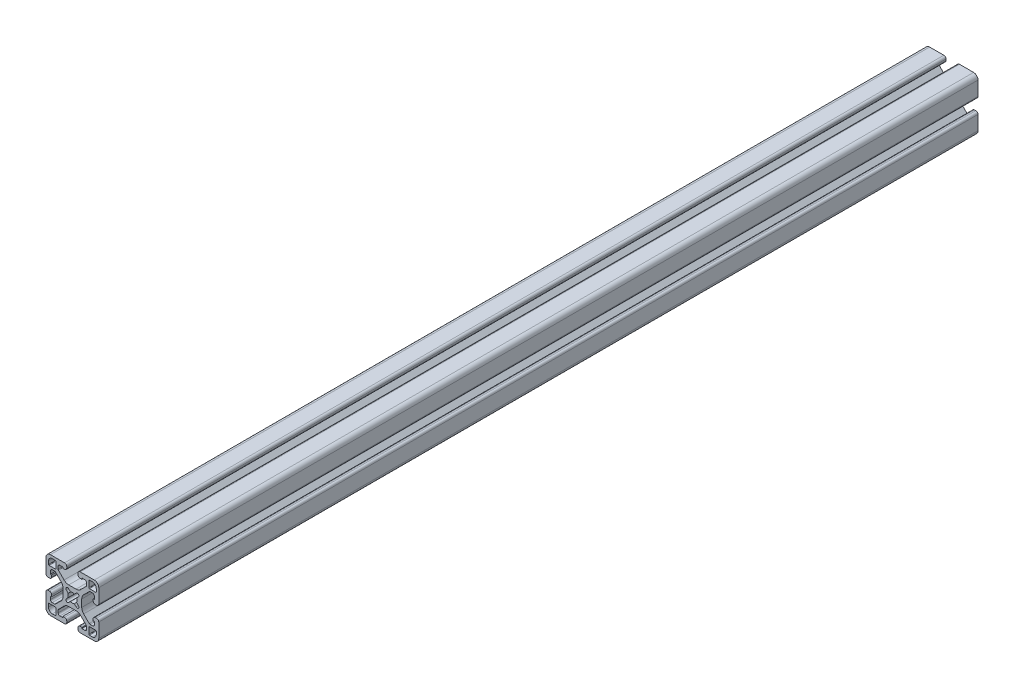
SolidWorks part; units mm, degrees
ref_plane "Front Plane" through (0, 0, 0) normal (0, 0, 1) x (1, 0, 0)
ref_plane "Top Plane" through (0, 0, 0) normal (0, 1, 0) x (1, 0, 0)
ref_plane "Right Plane" through (0, 0, 0) normal (1, 0, 0) x (0, 0, -1)
sketch "Sketch2" plane through (0, 0, 0) normal (0, 0, 1) x (1, 0, 0)
  line L0 (0, 19.05) -> (0, -19.05) construction
  line L1 (-19.05, 0) -> (19.05, 0) construction
  line L2 (4.064, -19.05) -> (19.05, -19.05)
  line L3 (19.05, -19.05) -> (19.05, -4.064)
  line L4 (4.064, -19.05) -> (4.064, -14.986)
  line L5 (4.064, -14.986) -> (12.8307, -14.986)
  line L6 (12.8307, -14.986) -> (4.6011, -6.7564)
  line L7 (0, 0) -> (19.05, -19.05) construction
  line L8 (19.05, -4.064) -> (14.986, -4.064)
  line L9 (14.986, -4.064) -> (14.986, -12.8307)
  line L10 (14.986, -12.8307) -> (6.7564, -4.6011)
  circle A0 centre (0, 0) radius 3.3274
  arc A1 (8.4883, -14.986) -> (9.7602, -11.9154) centre (8.4883, -13.1873) ccw construction
  point P8 (0, -6.7564)
  point P20 (0, 19.05)
  point P28 (19.05, 0)
  dimension "D1" = 3.048
  dimension "Center Hole Diameter" = 6.6548
  dimension "Rail Height" = 38.1
  dimension "Rail Width" = 38.1
  dimension "T Slot Width" = 8.128
  dimension "Slot Inner Width" = 20.574
  dimension "Thickness" = 4.064
  dimension "T Slot Depth" = 12.2936
sketch "Sketch3" plane through (0, 0, 0) normal (1, 0, 0) x (0, 0, -1)
  line L0 (-317.5, -19.05) -> (317.5, -19.05) construction
  line L1 (-274.066, 0) -> (274.066, 0) construction
  point P6 (-295.783, -19.05)
  dimension "Length" = 635
  dimension "D1" = 548.132
  dimension "Bore Hole Center to End of Rail" = 21.717
sketch "Sketch4" plane through (0, 0, 0) normal (0, 0, 1) x (1, 0, 0)
  line L1 (2.73, -4.3464) -> (1.4014, -3.0179)
  line L2 (15.8242, -6.858) -> (15.8242, -9.017)
  line L3 (14.5542, -10.287) -> (12.8105, -10.287)
  line L7 (4.3464, -2.73) -> (3.0179, -1.4014)
  line L9 (0, 0) -> (4.3464, -4.3464) construction
  line L23 (17.4752, -4.064) -> (16.5608, -4.064)
  line L24 (14.986, -5.6388) -> (14.986, -6.858)
  line L25 (12.1819, -10.0266) -> (8.1476, -5.9923)
  line L26 (6.7564, -2.6337) -> (6.7564, 0)
  line L27 (6.7564, 0) -> (3.3274, 0)
  line L28 (-19.05, 0) -> (19.05, 0) construction
  line L29 (0, -3.3274) -> (0, -6.7564)
  line L30 (0, 19.05) -> (0, -19.05) construction
  line L31 (0, -6.7564) -> (2.6337, -6.7564)
  line L32 (5.9923, -8.1476) -> (10.0266, -12.1819)
  line L33 (10.287, -12.8105) -> (10.287, -14.5542)
  line L34 (9.017, -15.8242) -> (6.858, -15.8242)
  line L35 (6.858, -15.8242) -> (6.858, -14.986)
  line L36 (6.858, -14.986) -> (5.6388, -14.986)
  line L37 (4.064, -16.5608) -> (4.064, -17.4752)
  line L39 (14.986, -6.858) -> (15.8242, -6.858)
  line L43 (14.986, -12.8307) -> (6.7564, -4.6011) construction
  line L44 (12.8307, -14.986) -> (4.6011, -6.7564) construction
  line L45 (15.875, -19.05) -> (5.6388, -19.05)
  line L46 (4.064, -19.05) -> (19.05, -19.05) construction
  line L48 (19.05, -15.875) -> (19.05, -5.6388)
  line L49 (19.05, -19.05) -> (19.05, -4.064) construction
  line L51 (4.064, -19.05) -> (4.064, -14.986) construction
  line L52 (19.05, -4.064) -> (14.986, -4.064) construction
  line L53 (4.064, -14.986) -> (12.8307, -14.986) construction
  arc A1 (15.875, -19.05) -> (19.05, -15.875) centre (15.875, -15.875) ccw
  arc A10 (9.017, -15.8242) -> (10.287, -14.5542) centre (9.017, -14.5542) ccw
  circle A12 centre (0, 0) radius 3.3274 construction
  arc A13 (0, -3.3274) -> (1.4014, -3.0179) centre (0, 0) ccw
  arc A14 (5.6388, -19.05) -> (4.064, -17.4752) centre (5.6388, -17.4752) cw
  arc A15 (4.064, -16.5608) -> (5.6388, -14.986) centre (5.6388, -16.5608) cw
  arc A16 (8.4883, -14.986) -> (9.7602, -11.9154) centre (8.4883, -13.1873) ccw construction
  arc A17 (14.986, -5.6388) -> (16.5608, -4.064) centre (16.5608, -5.6388) cw
  arc A18 (17.4752, -4.064) -> (19.05, -5.6388) centre (17.4752, -5.6388) cw
  arc A19 (14.5542, -10.287) -> (15.8242, -9.017) centre (14.5542, -9.017) ccw
  arc A20 (10.287, -12.8105) -> (10.0266, -12.1819) centre (9.398, -12.8105) ccw
  arc A21 (12.1819, -10.0266) -> (12.8105, -10.287) centre (12.8105, -9.398) ccw
  arc A22 (5.9923, -8.1476) -> (2.6337, -6.7564) centre (2.6337, -11.5062) ccw
  arc A23 (8.1476, -5.9923) -> (6.7564, -2.6337) centre (11.5062, -2.6337) cw
  arc A25 (3.0179, -1.4014) -> (3.3274, 0) centre (0, 0) ccw
  arc A26 (2.73, -4.3464) -> (4.3464, -2.73) centre (3.5382, -3.5382) ccw
  dimension "D1" = 3.175
  dimension "D2" = 6.1468
  dimension "D5" = 1.5748
  dimension "D8" = 1.27
  dimension "D9" = 0.889
  dimension "D10" = 4.7498
  dimension "D3" = 1.143
  dimension "D6" = 0.8382
  dimension "D7" = 3.429
extrude "Boss-Extrude1" add sketch "Sketch4" along normal mid plane 635
sketch "Sketch5" plane through (0, 0, 0) normal (0, 0, 1) x (1, 0, 0)
  line L1 (4.064, -19.05) -> (19.05, -19.05) construction
  line L3 (0, 0) -> (19.05, -19.05) construction
  line L6 (16.8656, -11.8618) -> (12.2428, -11.8618)
  line L7 (11.8618, -12.2428) -> (11.8618, -16.8656)
  line L8 (12.2428, -17.2466) -> (14.4526, -17.2466)
  line L9 (17.2466, -14.4526) -> (17.2466, -12.2428)
  arc A8 (14.4526, -17.2466) -> (17.2466, -14.4526) centre (14.4526, -14.4526) ccw
  arc A9 (12.2428, -17.2466) -> (11.8618, -16.8656) centre (12.2428, -16.8656) cw
  arc A10 (11.8618, -12.2428) -> (12.2428, -11.8618) centre (12.2428, -12.2428) cw
  arc A11 (17.2466, -12.2428) -> (16.8656, -11.8618) centre (16.8656, -12.2428) ccw
  dimension "D6" = 2.794
  dimension "D7" = 0.381
  dimension "D4" = 5.3848
  dimension "D5" = 5.3848
  dimension "D8" = 1.8034
extrude "Cut-Extrude1" cut sketch "Sketch5" against normal through all both and the other way through all
mirror "Mirror1" about plane through (0, 0, 0) normal (1, 0, 0) of bodies 137 134
mirror "Mirror2" about plane through (0, 0, 0) normal (0, 1, 0) of bodies 135
sketch "Sketch6" plane through (0, 0, 0) normal (0, 0, 1) x (1, 0, 0)
  line L0 (4.064, -19.05) -> (4.064, -14.986) construction
  line L1 (0, 19.05) -> (0, -19.05) construction
  line L2 (0, 19.05) -> (0, -19.05) construction
  circle A0 centre (0, 0) radius 3.3274 construction
  circle A1 centre (0, 0) radius 3.3274
  arc A2 (-17.4752, -4.064) -> (-19.05, -5.6388) centre (-17.4752, -5.6388) ccw construction
  arc A3 (-19.05, 5.6388) -> (-17.4752, 4.064) centre (-17.4752, 5.6388) ccw construction
  arc A4 (-17.4752, -4.064) -> (-19.05, -5.6388) centre (-17.4752, -5.6388) ccw
  arc A5 (-19.05, 5.6388) -> (-17.4752, 4.064) centre (-17.4752, 5.6388) ccw
  arc A6 (-5.6388, -19.05) -> (-4.064, -17.4752) centre (-5.6388, -17.4752) ccw construction
  arc A7 (4.064, -17.4752) -> (5.6388, -19.05) centre (5.6388, -17.4752) ccw construction
  arc A8 (-5.6388, -19.05) -> (-4.064, -17.4752) centre (-5.6388, -17.4752) ccw
  arc A9 (4.064, -17.4752) -> (5.6388, -19.05) centre (5.6388, -17.4752) ccw
  arc A10 (-8.1476, -5.9923) -> (-6.7564, -2.6337) centre (-11.5062, -2.6337) ccw construction
  arc A11 (-8.1476, -5.9923) -> (-6.7564, -2.6337) centre (-11.5062, -2.6337) ccw
  arc A12 (-5.9923, 8.1476) -> (-2.6337, 6.7564) centre (-2.6337, 11.5062) ccw construction
  arc A13 (-5.9923, 8.1476) -> (-2.6337, 6.7564) centre (-2.6337, 11.5062) ccw
  point P3 (4.064, 19.05)
  point P4 (-4.064, 19.05)
  point P5 (19.05, -19.05)
  point P8 (-19.05, -19.05)
  point P13 (19.05, 19.05)
  point P14 (0, -3.3274)
  point P15 (4.6011, -6.7564)
  point P19 (-4.6011, -6.7564)
  point P22 (-19.05, 19.05)
  point P23 (0, 3.3274)
  point P28 (-2.6337, 6.7564)
  point P44 (-17.4752, -4.064)
  point P51 (-17.4752, 4.064)
  point P57 (-4.064, -17.4752)
  point P58 (4.064, -17.4752)
  point P60 (-6.7564, -2.6337)
sketch "Sketch8" plane through (0, 0, 0) normal (1, 0, 0) x (0, 0, -1)
  point P14 (317.5, 19.05)
  point P15 (-317.5, 19.05)
  point P16 (274.066, 0)
  point P17 (-274.066, 0)
equation "\"D1@Boss-Extrude1\"=\"Length@Sketch3\""
equation "\"D1@Sketch3\"=\"Length@Sketch3\"-\"Bore Hole Center to End of Rail@Sketch3\"*4"
equation "\"D5@Sketch5\"=\"D4@Sketch5\""
